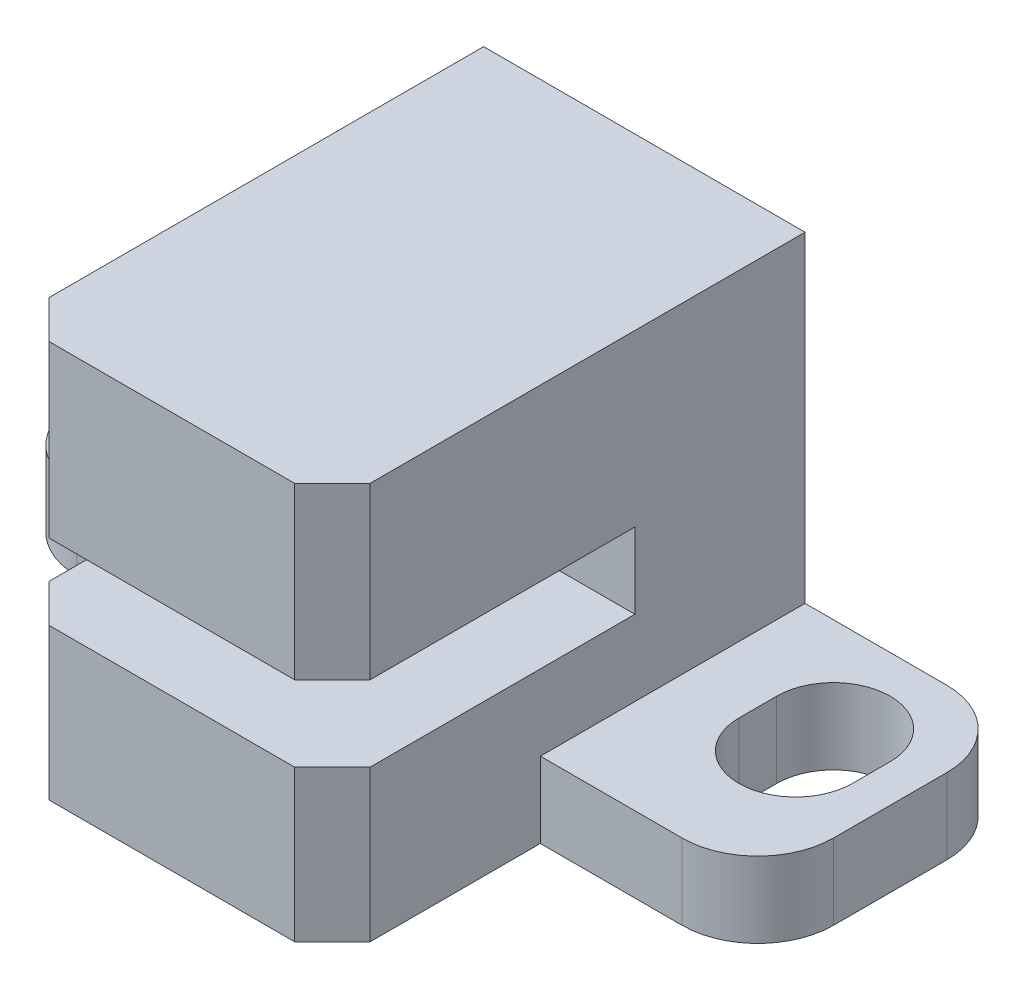
SolidWorks part; units mm, degrees
ref_plane "Front Plane" through (0, 0, 0) normal (0, 0, 1) x (1, 0, 0)
ref_plane "Top Plane" through (0, 0, 0) normal (0, 1, 0) x (1, 0, 0)
ref_plane "Right Plane" through (0, 0, 0) normal (1, 0, 0) x (0, 0, -1)
sketch "Sketch1" plane through (0, 0, 0) normal (0, 0, 1) x (1, 0, 0)
  line L1 (-4.25, 5.25) -> (4.25, 5.25)
  line L2 (-4.25, 5.25) -> (-4.25, -5.25)
  line L3 (-4.25, -5.25) -> (4.25, -5.25)
  line L4 (4.25, 5.25) -> (4.25, -5.25)
  line L5 (-4.25, 5.25) -> (4.25, -5.25) construction
  line L6 (-4.25, -5.25) -> (4.25, 5.25) construction
  point P0 (0, 0)
  dimension "D1" = 8.5
  dimension "D2" = 10.5
extrude "Boss-Extrude1" add sketch "Sketch1" along normal blind 12.5
sketch "Sketch2" plane through (0, 0, 12.5) normal (0, 0, 1) x (1, 0, 0)
  line L0 (-4.25, 5.25) -> (-4.25, -5.25) construction
  line L1 (-4.25, 0.75) -> (4.25, 0.75)
  line L2 (-4.25, 0.75) -> (-4.25, -1.25)
  line L3 (-4.25, -1.25) -> (4.25, -1.25)
  line L4 (4.25, 0.75) -> (4.25, -1.25)
  line L5 (4.25, -5.25) -> (4.25, 5.25) construction
  line L6 (-4.25, -5.25) -> (4.25, -5.25) construction
  dimension "D1" = 2
  dimension "D2" = 4
extrude "Cut-Extrude1" cut sketch "Sketch2" against normal blind 8
sketch "Sketch3" plane through (0, -5.25, 0) normal (0, -1, 0) x (1, 0, 0)
  line L0 (7.5, 2.5) -> (7.5, 3.5) construction
  line L1 (4.25, 0) -> (8, 0)
  line L2 (4.25, 0) -> (4.25, 7)
  line L3 (4.25, 7) -> (8, 7)
  line L4 (10, 2) -> (10, 5)
  line L5 (6, 2.5) -> (6, 3.5)
  line L6 (9, 2.5) -> (9, 3.5)
  line L7 (0, 0) -> (0, 12.5) construction
  line L8 (-4.25, 0) -> (4.25, 0) construction
  line L9 (-4.25, 12.5) -> (4.25, 12.5) construction
  line L10 (-10, 2) -> (-10, 5)
  line L11 (-4.25, 7) -> (-8, 7)
  line L12 (-4.25, 0) -> (-4.25, 7)
  line L13 (-4.25, 0) -> (-8, 0)
  line L14 (-7.5, 2.5) -> (-7.5, 3.5) construction
  line L15 (-6, 2.5) -> (-6, 3.5)
  line L16 (-9, 2.5) -> (-9, 3.5)
  arc A0 (6, 2.5) -> (9, 2.5) centre (7.5, 2.5) ccw
  arc A1 (9, 3.5) -> (6, 3.5) centre (7.5, 3.5) ccw
  arc A2 (-6, 2.5) -> (-9, 2.5) centre (-7.5, 2.5) cw
  arc A3 (-9, 3.5) -> (-6, 3.5) centre (-7.5, 3.5) cw
  arc A4 (8, 7) -> (10, 5) centre (8, 5) cw
  arc A5 (10, 2) -> (8, 0) centre (8, 2) cw
  arc A6 (-8, 0) -> (-10, 2) centre (-8, 2) cw
  arc A7 (-8, 7) -> (-10, 5) centre (-8, 5) ccw
  point P7 (7.5, 3)
  point P26 (-7.5, 3)
  point P33 (10, 7)
  point P36 (10, 0)
  point P39 (-10, 0)
  point P42 (-10, 7)
  dimension "D3" = 1.5
  dimension "D7" = 2
  dimension "D1" = 7
  dimension "D2" = 10
  dimension "D4" = 1
  dimension "D5" = 2
  dimension "D6" = 7.5
extrude "Boss-Extrude2" add sketch "Sketch3" against normal blind 2
chamfer "Chamfer1" distance 1 angle 45 4 edges at (4.25, -3.25, 12.5) (4.25, 3, 12.5) (-4.25, -3.25, 12.5) (-4.25, 3, 12.5)
